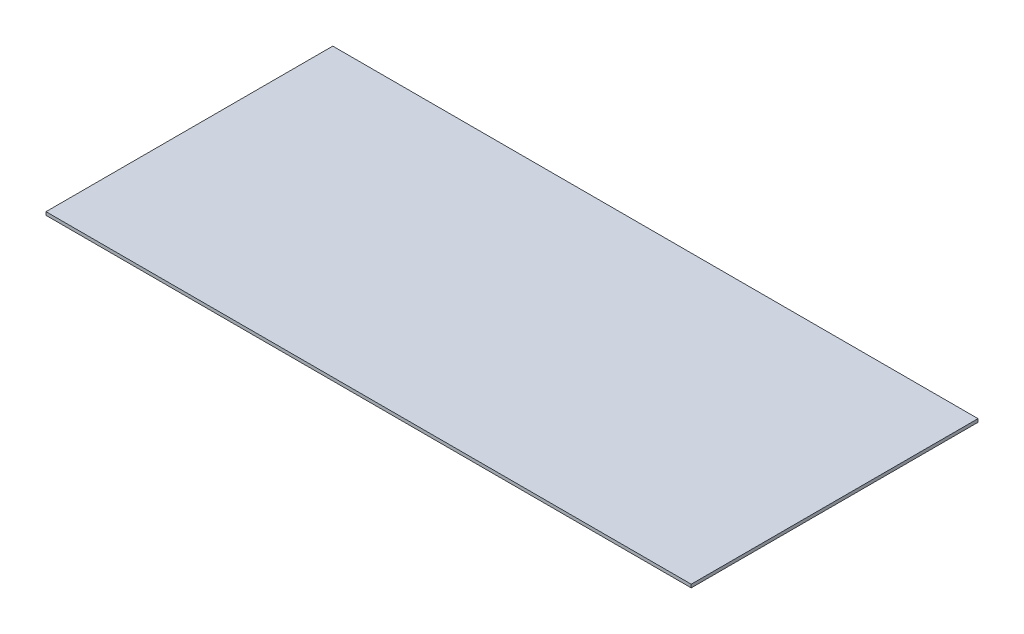
SolidWorks part; units mm, degrees
ref_plane "Front Plane" through (0, 0, 0) normal (0, 0, 1) x (1, 0, 0)
ref_plane "Top Plane" through (0, 0, 0) normal (0, 1, 0) x (1, 0, 0)
ref_plane "Right Plane" through (0, 0, 0) normal (1, 0, 0) x (0, 0, -1)
sketch "Text / Border" plane through (0, 0, 0) normal (0, 1, 0) x (1, 0, 0)
  line L1 (0, 0) -> (180, 0)
  line L2 (0, 0) -> (0, 80)
  line L3 (0, 80) -> (180, 80)
  line L4 (180, 0) -> (180, 80)
  dimension "D1" = 80
  dimension "D2" = 180
sketch "LED Guide" plane through (0, 0, 0) normal (0, 1, 0) x (1, 0, 0)
  line L0 (187.7196, 75.5) -> (198.2196, 75.5)
  line L1 (187.7196, 75.5) -> (187.7196, 15.5)
  line L2 (187.7196, 15.5) -> (198.2196, 15.5)
  line L3 (198.2196, 75.5) -> (198.2196, 15.5)
  line L4 (0, 80) -> (180, 80) construction
  dimension "D1" = 60
  dimension "D2" = 4.5
  dimension "D4" = 10.5
extrude "Body" add sketch "Text / Border" along normal blind 0.9
